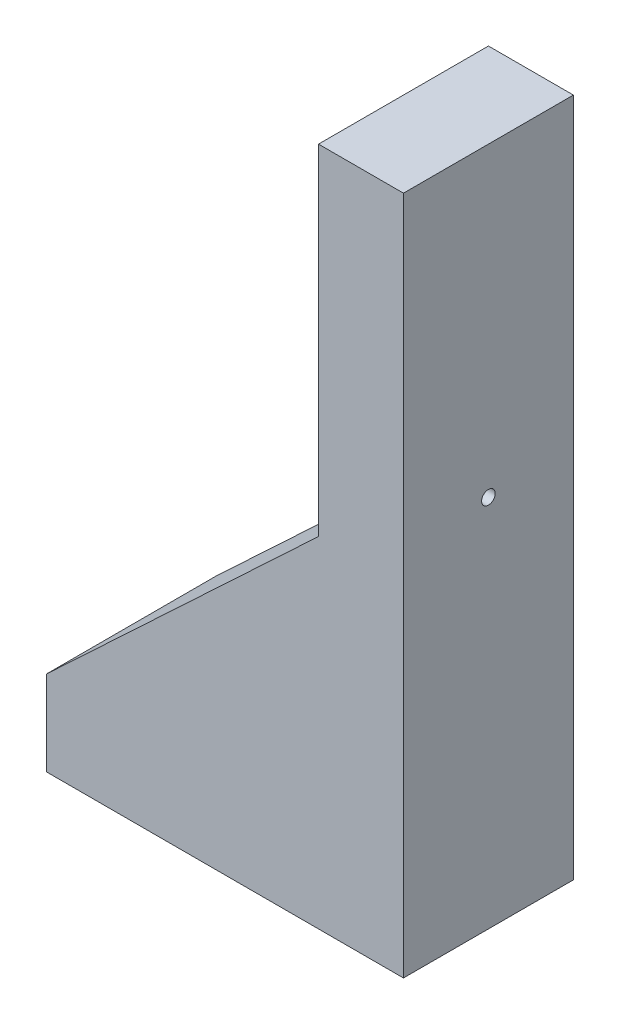
SolidWorks part; units mm, degrees
material "Beech"
ref_plane "Front Plane" through (0, 0, 0) normal (0, 0, 1) x (1, 0, 0)
ref_plane "Top Plane" through (0, 0, 0) normal (0, 1, 0) x (1, 0, 0)
ref_plane "Right Plane" through (0, 0, 0) normal (1, 0, 0) x (0, 0, -1)
sketch "Sketch1" plane through (0, 0, 0) normal (0, 0, 1) x (1, 0, 0)
  line L0 (0, 97.8193) -> (0, -102.1807)
  line L1 (0, -102.1807) -> (-105, -102.1807)
  line L2 (-105, -102.1807) -> (-105, -77.1807)
  line L3 (-105, -77.1807) -> (-25, -2.1807)
  line L4 (-25, -2.1807) -> (-25, 97.8193)
  line L5 (-25, 97.8193) -> (0, 97.8193)
  dimension "D1" = 200
  dimension "D2" = 25
  dimension "D3" = 25
  dimension "D4" = 105
  dimension "D5" = 100
extrude "Boss-Extrude1" add sketch "Sketch1" along normal blind 50
sketch "Sketch2" plane through (0, 0, 0) normal (1, 0, 0) x (0, 0, -1)
  line L0 (0, 0) -> (-50, 0) construction
  line L1 (-50, -102.1807) -> (-50, 97.8193) construction
  line L2 (-25, -102.1807) -> (-25, 0) construction
  line L3 (-50, -102.1807) -> (0, -102.1807) construction
  line L4 (-25, 0) -> (-25, 59.9281) construction
  circle A0 centre (-25, 7.8193) radius 2
  dimension "D1" = 4
  dimension "D2" = 110
extrude "Cut-Extrude1" cut sketch "Sketch2" against normal blind 25
